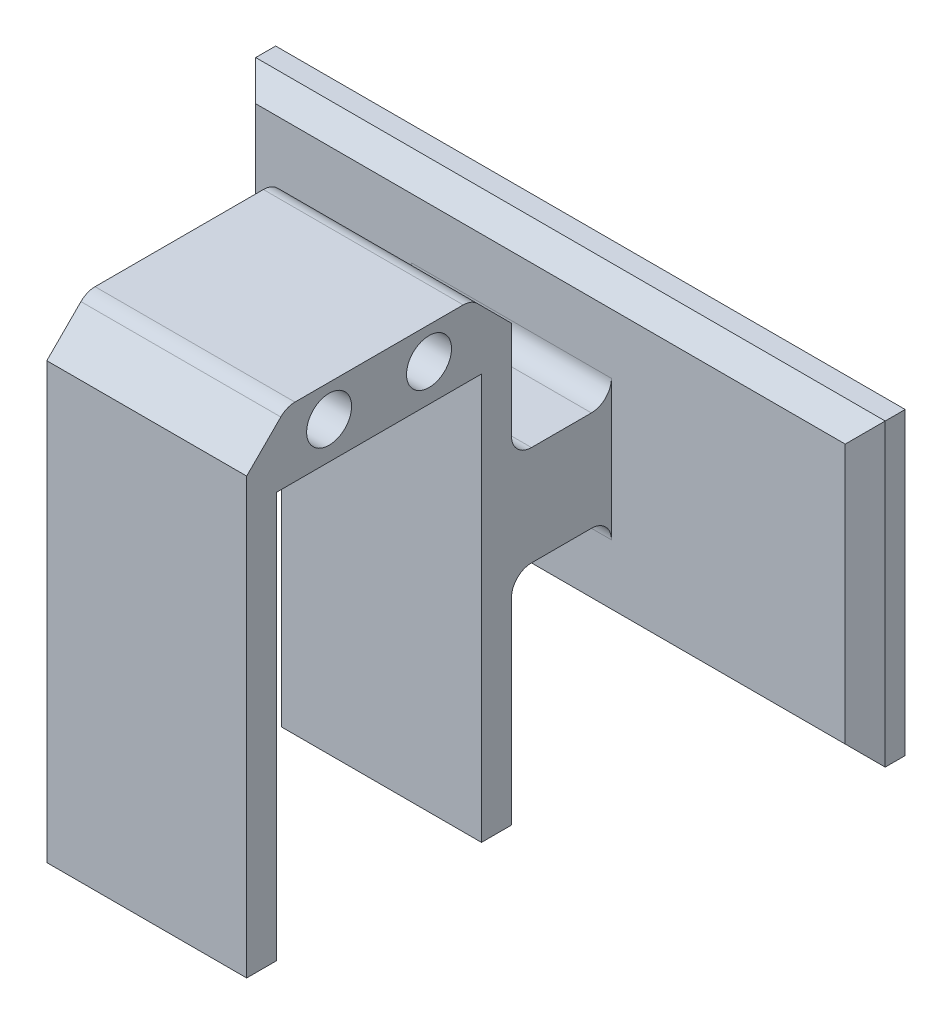
SolidWorks part; units mm, degrees
ref_plane "Front Plane" through (0, 0, 0) normal (0, 0, 1) x (1, 0, 0)
ref_plane "Top Plane" through (0, 0, 0) normal (0, 1, 0) x (1, 0, 0)
ref_plane "Right Plane" through (0, 0, 0) normal (1, 0, 0) x (0, 0, -1)
sketch "Sketch1" plane through (0, 0, 0) normal (1, 0, 0) x (0, 0, -1)
  line L0 (-10.25, 20.3) -> (10.25, 20.3)
  line L1 (-10.25, -20.3) -> (10.25, -20.3)
  line L2 (-10.25, -20.3) -> (-10.25, 20.3)
  line L4 (10.25, -20.3) -> (10.25, 20.3)
  line L5 (-10.25, -20.3) -> (-13.25, -20.3)
  line L6 (-13.25, -20.3) -> (-13.25, 29.7)
  line L7 (-13.25, 29.7) -> (13.25, 29.7)
  line L8 (10.25, -20.3) -> (13.25, -20.3)
  line L11 (-10.05, 20.1) -> (10.05, 20.1)
  line L13 (13.25, -20.3) -> (13.25, 29.7)
  point P5 (0, 20.3)
  point P6 (-10.25, 0)
  line B0 (-8.8772, 20.1) -> (-10.8742, 20.1) construction
  line B1 (7.4, 20.1) -> (11.2713, 20.1) construction
  line B2 (10.05, 18.0597) -> (10.05, 22.3295) construction
  line B3 (-3.2, -20.1) -> (-12.1258, -20.1) construction
  line B4 (-10.05, -15.1145) -> (-10.05, -21.3251) construction
  line B5 (-10.05, -20.1) -> (10.05, -20.1)
  line B6 (-10.05, -20.1) -> (-10.05, 20.1)
  line B7 (10.05, -20.1) -> (10.05, 20.1)
  circle B8 centre (-5, 24) radius 2.25
  circle B9 centre (5, 24) radius 2.25
  dimension "D1" = 0.2
  dimension "D2" = 0.2
  dimension "D3" = 0.2
  dimension "D4" = 0.2
  dimension "D5" = 3
  dimension "D6" = 50
  dimension "D7" = 3
sketch_block_instance "Block1-1"
sketch_block "Block1"
extrude "Boss-Extrude1" add sketch "Sketch1" along normal blind 20 contours L8 L13 L7 L6 L5 L2 L0 L4 B9 B8
sketch "Sketch2" plane through (0, 0, 0) normal (-1, 0, 0) x (0, 0, 1)
  circle A0 centre (-5, 24) radius 2.25
  circle A1 centre (5, 24) radius 2.25
extrude "Boss-Extrude2" add sketch "Sketch2" against normal blind 10
sketch "Sketch4" plane through (20, 0, 0) normal (1, 0, 0) x (0, 0, -1)
  line L0 (13.25, -20.3) -> (13.25, 29.7) construction
  line L1 (-13.25, 29.7) -> (13.25, 29.7)
  line L2 (-13.25, 29.7) -> (-13.25, 27.2)
  line L3 (-13.25, 27.2) -> (13.25, 27.2)
  line L4 (13.25, 29.7) -> (13.25, 27.2)
  dimension "D1" = 2.5
extrude "Cut-Extrude1" cut sketch "Sketch4" against normal through all
chamfer "Chamfer2" distance 4 angle 45 1 edges at (10, 27.2, -13.25)
chamfer "Chamfer3" distance 4 angle 45 1 edges at (10, 27.2, 13.25)
fillet "Fillet4" radius 2 2 edges at (10, 27.2, -9.25) (10, 27.2, 9.25)
sketch "Sketch7" plane through (20, 0, 0) normal (1, 0, 0) x (0, 0, -1)
  line L0 (13.25, -20.3) -> (13.25, 23.2) construction
  line L3 (23.25, 1.4232) -> (13.25, 1.4232)
  line L6 (13.25, 11.4232) -> (23.25, 11.4232)
  line L8 (23.25, 11.4232) -> (23.25, 1.4232)
  line L9 (13.25, 11.4232) -> (13.25, 1.4232)
  dimension "D1" = 10
extrude "Boss-Extrude5" add sketch "Sketch7" against normal up to surface (20 mm away) up to face at (0, 9.4758, 0)
fillet "Fillet6" radius 2 2 edges at (10, 11.4232, -13.25) (10, 1.4232, -13.25)
sketch "Sketch8" plane through (0, 0, -23.25) normal (0, 0, -1) x (-1, 0, 0)
  line L1 (-45.4, 21.4232) -> (17.6, 21.4232)
  line L2 (-45.4, 21.4232) -> (-45.4, -8.5768)
  line L3 (-45.4, -8.5768) -> (17.6, -8.5768)
  line L4 (17.6, 21.4232) -> (17.6, -8.5768)
  line L5 (0, 11.4232) -> (-20, 11.4232) construction
  line L7 (-13.9, 11.4232) -> (-13.9, 1.4232) construction
  line L8 (-20, 1.4232) -> (-20, 11.4232) construction
  line L9 (-20, 6.4232) -> (0, 6.4232) construction
  line L10 (0, 11.4232) -> (0, 1.4232) construction
  line L11 (0, 1.4232) -> (-20, 1.4232) construction
  point P10 (-13.9, 21.4232)
  point P17 (-45.4, 6.4232)
  dimension "D1" = 63
  dimension "D2" = 30
  dimension "D3" = 6.1
extrude "Boss-Extrude6" add sketch "Sketch8" along normal blind 4
chamfer "Chamfer4" distance 2 angle 45 4 edges at (-17.6, 6.4232, -23.25) (13.9, -8.5768, -23.25) (45.4, 6.4232, -23.25) (13.9, 21.4232, -23.25)
fillet "Fillet7" radius 2 2 edges at (10, 11.4232, -23.25) (10, 1.4232, -23.25)
